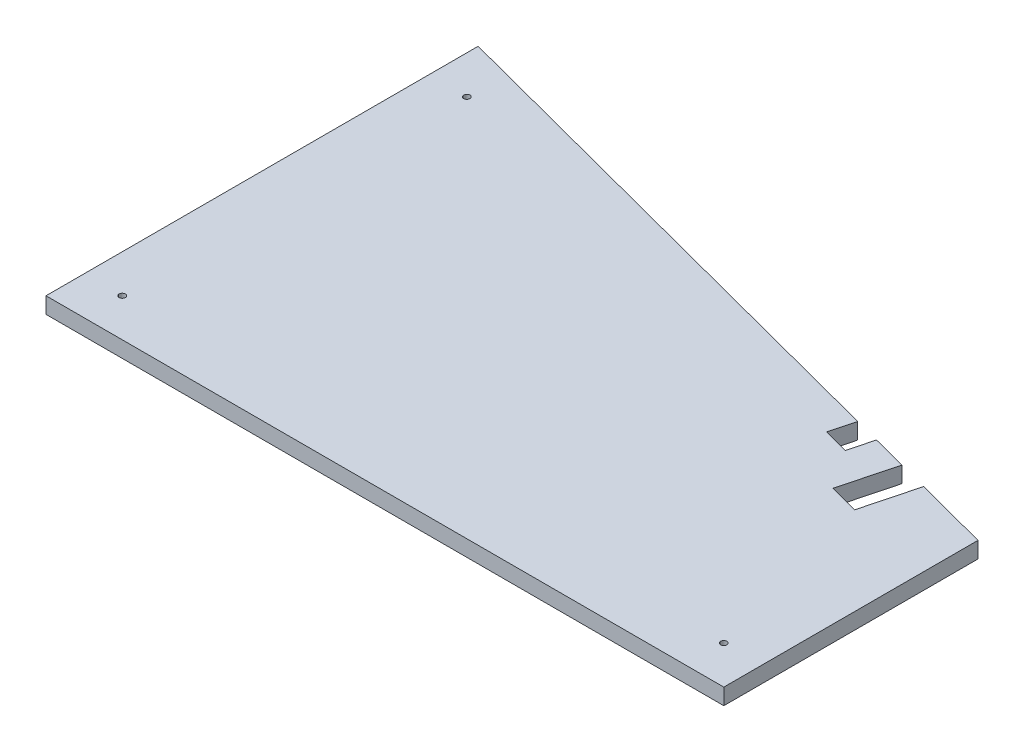
SolidWorks part; units mm, degrees
material "Balsa"
ref_plane "Front Plane" through (0, 0, 0) normal (0, 0, 1) x (1, 0, 0)
ref_plane "Top Plane" through (0, 0, 0) normal (0, 1, 0) x (1, 0, 0)
ref_plane "Right Plane" through (0, 0, 0) normal (1, 0, 0) x (0, 0, -1)
sketch "Sketch2" plane through (0, 0, 0) normal (0, 1, 0) x (1, 0, 0)
  line L0 (0, 0) -> (266.65, 0)
  line L1 (266.65, 0) -> (266.65, 100)
  line L2 (266.65, 100) -> (237.6332, 107.6174)
  line L4 (226.0265, 110.6643) -> (220.3896, 89.1919)
  line L5 (220.3896, 89.1919) -> (231.9963, 86.1449)
  line L6 (231.9963, 86.1449) -> (237.6332, 107.6174)
  line L7 (226.0265, 110.6643) -> (212.4853, 114.2191)
  line L8 (209.9462, 104.5469) -> (199.9462, 107.172)
  line L9 (199.9462, 107.172) -> (202.4853, 116.8443)
  line L10 (209.9462, 104.5469) -> (212.4853, 114.2191)
  line L11 (202.4853, 116.8443) -> (0, 170)
  line L16 (0, 170) -> (0, 0)
  dimension "D1" = 170
  dimension "D2" = 100
  dimension "D3" = 266.65
  dimension "D4" = 30
  dimension "D5" = 12
  dimension "D6" = 14
  dimension "D7" = 10
  dimension "D8" = 10
  dimension "D9" = 22.2
extrude "Boss-Extrude1" add sketch "Sketch2" along normal blind 6.35
sketch "Sketch3" plane through (0, 6.35, 0) normal (0, 1, 0) x (1, 0, 0)
  line L0 (0, 0) -> (266.65, 0) construction
  line L1 (0, 170) -> (0, 0) construction
  line L3 (202.4853, 116.8443) -> (0, 170) construction
  line L4 (266.65, 0) -> (266.65, 100) construction
  circle A0 centre (15, 150.554) radius 1.225
  circle A1 centre (15, 15) radius 1.225
  circle A2 centre (251.65, 15) radius 1.225
  dimension "D1" = 2.45
  dimension "D2" = 2.45
  dimension "D3" = 2.45
  dimension "D4" = 15
  dimension "D5" = 15
  dimension "D6" = 15
  dimension "D7" = 15
  dimension "D8" = 15
  dimension "D9" = 15
extrude "Cut-Extrude1" cut sketch "Sketch3" against normal through all
